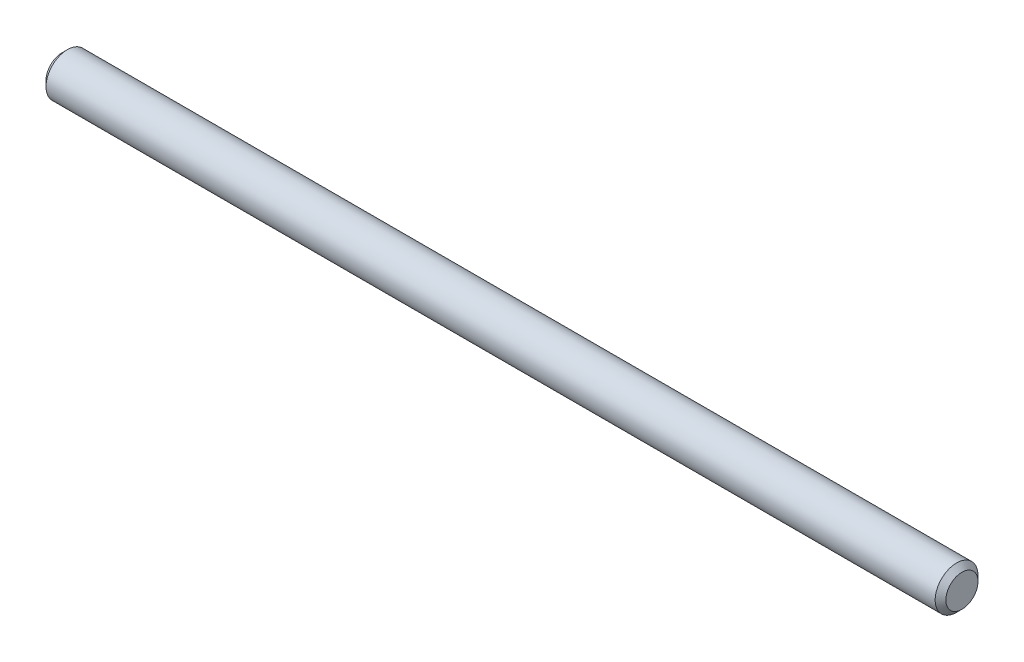
SolidWorks part; units mm, degrees
ref_plane "Front Plane" through (0, 0, 0) normal (0, 0, 1) x (1, 0, 0)
ref_plane "Top Plane" through (0, 0, 0) normal (0, 1, 0) x (1, 0, 0)
ref_plane "Right Plane" through (0, 0, 0) normal (1, 0, 0) x (0, 0, -1)
sketch "Sketch1" plane through (0, 0, 0) normal (1, 0, 0) x (0, 0, -1)
  circle A0 centre (0, 0) radius 2
extrude "Boss-Extrude1" add sketch "Sketch1" along normal mid plane 84
cosmetic thread "Cosmetic Thread1" parameters "D1"=8, "D2"=3.22
cosmetic thread "Cosmetic Thread2" parameters "D1"=8, "D2"=3.22
chamfer "Chamfer1" distance 0.5 angle 45 2 edges at (42, 0, -2) (-42, 0, -2)
